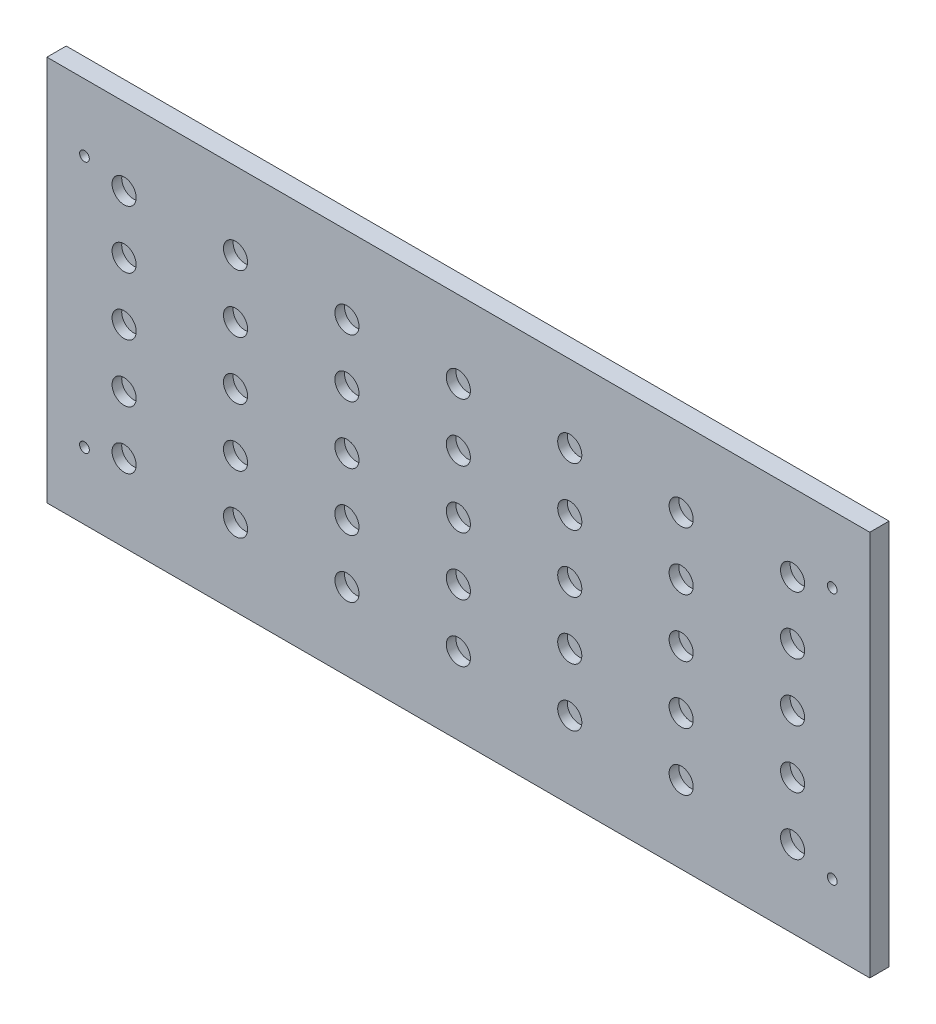
SolidWorks part; units mm, degrees
ref_plane "Front Plane" through (0, 0, 0) normal (0, 0, 1) x (1, 0, 0)
ref_plane "Top Plane" through (0, 0, 0) normal (0, 1, 0) x (1, 0, 0)
ref_plane "Right Plane" through (0, 0, 0) normal (1, 0, 0) x (0, 0, -1)
sketch "Sketch1" plane through (0, 0, 0) normal (0, 0, 1) x (1, 0, 0)
  line L0 (135.35, 127) -> (135.35, 0) construction
  line L1 (0, 0) -> (270.7, 0)
  line L2 (0, 0) -> (0, 127)
  line L3 (0, 127) -> (270.7, 127)
  line L4 (270.7, 0) -> (270.7, 127)
  line L5 (0, 63.5) -> (270.7, 63.5) construction
  circle A3 centre (12.35, 105) radius 1.6
  circle A7 centre (258.35, 105) radius 1.6
  circle A8 centre (258.35, 22) radius 1.6
  circle A9 centre (12.35, 22) radius 1.6
  dimension "D11" = 3.2
  dimension "D1" = 127
  dimension "D2" = 270.7
  dimension "D12" = 12.35
  dimension "D13" = 22
extrude "Wall" add sketch "Sketch1" along normal blind 6.35
sketch "Sketch2" plane through (0, 0, 6.35) normal (0, 0, 1) x (1, 0, 0)
  line L0 (135.35, 127) -> (135.35, 98.425) construction
  line L1 (270.7, 127) -> (0, 127) construction
  line L2 (135.35, 98.425) -> (66.6667, 98.425) construction
  line L3 (135.35, 98.425) -> (204.0333, 98.425) construction
  line L4 (0, 127) -> (0, 0) construction
  circle A0 centre (135.35, 98.425) radius 3.9687
  circle A1 centre (66.6667, 98.425) radius 3.9688
  circle A2 centre (204.0333, 98.425) radius 3.9687
  dimension "D2" = 7.9375
  dimension "D1" = 28.575
  dimension "D3" = 66.6667
extrude "RodSupportCutouts" [suppressed] cut sketch "Sketch2" against normal up to next
sketch "Sketch3" plane through (0, 0, 6.35) normal (0, 0, 1) x (1, 0, 0)
  line L1 (25.4, 88.9) -> (245.3, 88.9)
  line L2 (25.4, 88.9) -> (25.4, 114.3)
  line L3 (25.4, 114.3) -> (245.3, 114.3)
  line L4 (245.3, 88.9) -> (245.3, 114.3)
  line L5 (25.4, 88.9) -> (245.3, 114.3) construction
  line L6 (25.4, 114.3) -> (245.3, 88.9) construction
  line L7 (270.7, 127) -> (0, 127) construction
  line L8 (0, 127) -> (0, 0) construction
  point P0 (135.35, 101.6)
  point P9 (135.35, 127)
  dimension "D1" = 25.4
  dimension "D2" = 25.4
  dimension "D3" = 25.4
extrude "CannulaLargeCutout" [suppressed] cut sketch "Sketch3" against normal up to next
sketch "Sketch4" [suppressed] plane through (0, 0, 9.525) normal (0, 0, 1) x (1, 0, 0)
  line L0 (6, 103.5) -> (194, 103.5) construction
  line L1 (6, 105) -> (6, 22) construction
  line L2 (194, 105) -> (194, 22) construction
  line L3 (200, 127) -> (0, 127) construction
  line L4 (0, 127) -> (0, 0) construction
  circle A0 centre (60, 103.5) radius 6.35
  circle A1 centre (20, 103.5) radius 6.35
  circle A2 centre (100, 103.5) radius 6.35
  circle A3 centre (140, 103.5) radius 6.35
  circle A4 centre (60, 63.5) radius 6.35
  circle A5 centre (100, 63.5) radius 6.35
  circle A6 centre (140, 63.5) radius 6.35
  circle A7 centre (60, 23.5) radius 6.35
  circle A8 centre (100, 23.5) radius 6.35
  circle A9 centre (140, 23.5) radius 6.35
  circle A10 centre (20, 63.5) radius 6.35
  circle A11 centre (20, 23.5) radius 6.35
  circle A12 centre (180, 103.5) radius 6.35
  circle A13 centre (180, 63.5) radius 6.35
  circle A14 centre (180, 23.5) radius 6.35
  point P42 (100, 127)
  point P45 (0, 63.5)
  dimension "D3" = 12.7
  dimension "D1" = 5
  dimension "D2" = 3
extrude "CannulaHoles" [suppressed] cut sketch "Sketch4" against normal up to next
ref_plane "LeftBoundary" through (25.4, 0, 0) normal (-1, 0, 0) x (0, 0, 1)
ref_plane "RightBoundary" through (245.3, 0, 0) normal (1, 0, 0) x (0, 0, -1)
ref_plane "TopBoundary" through (0, 101.6, 0) normal (0, 1, 0) x (1, 0, 0)
ref_plane "BottomBoundary" through (0, 25.4, 0) normal (0, -1, 0) x (-1, 0, 0)
sketch "Sketch5" plane through (0, 0, 6.35) normal (0, 0, 1) x (1, 0, 0)
  line L4 (25.4, 3.4925) -> (25.4, -3.4925) construction
  line L5 (3.4925, 101.6) -> (-3.4925, 101.6) construction
  circle A0 centre (25.4, 101.6) radius 3.9687
  dimension "D1" = 7.9375
extrude "RodSupportCutout" cut sketch "Sketch5" against normal blind 3.175 from surface at 0 starting at face at (135.35, 63.5, 6.35)
pattern_linear "SupportPattern" count 7 spacing 36.65 along (1, 0, 0) count 5 spacing 19.05 along (0, -1, 0) of "RodSupportCutout"
equation "\"Length\"= 283mm"
equation "\"Width\"= 225mm"
equation "\"WallThickness\"= 0.25in"
equation "\"UpperWaterJacketThickness\"= 28mm"
equation "\"SpacerHeight\"= 80.2mm"
equation "\"SpacerCornerWidth\"= 10mm"
equation "\"SpacerCornerHeight\"= 60.16mm"
equation "\"SpacerPegDiameter\"= 10mm"
equation "\"SpacerPegHeight\"= 10mm"
equation "\"TubingShort\"= 110mm"
equation "\"TubingLong\"= 175mm"
equation "\"PlateLength\"= 252mm"
equation "\"PlateWidth\"= 190mm"
equation "\"PlateHoleDiameter\"= 5.9mm"
equation "\"PlateHoleBottom\"= 2mm"
equation "\"PlateHoleSide\"= 1.55mm"
equation "\"PlateHoleSpacing\"= 3.1mm"
equation "\"PlateThickness\"= 1.55mm"
equation "\"ReservoirBottom\"= 12.5mm"
equation "\"ReservoirSupportWidth\"= 12mm"
equation "\"ReservoirSupportHeight\"= 15.1mm"
equation "\"ReservoirSupportPlacementHeight\"= 50mm"
equation "\"ReservoirHoleDiameter\"= 12.7mm"
equation "\"ReservoirHoleRight\"= 25mm"
equation "\"ReservoirHoleTop\"= \"ReservoirSupportPlacementHeight\""
equation "\"ReservoirHeight\"= 90mm"
equation "\"ReservoirPortBottom\"= 4mm"
equation "\"ReservoirPortTop\"= 10mm"
equation "\"ReservoirPortWidth\"= 101mm"
equation "\"CustomSpacerHeight\"= 5in"
equation "\"CustomSpacerRodHoleHeight\"= .75in"
equation "\"CustomSpacerRodHoleDiameter\"= .3125in"
equation "\"ScrewBlockSide\"= 12mm"
equation "\"ScrewBlockUpperHeight\"= 16mm"
equation "\"ScrewBlockLowerHeight\"= 16mm"
equation "\"InternalLength\"= 258mm"
equation "\"InternalWidth\"= 200mm"
equation "\"CustomSpacerPegHeight\"= 1in"
equation "\"CustomSpacerScrewBore\"=3.2mm"
equation "\"CustomSpacerScrewDepth\"=10mm"
equation "\"D1@Sketch1\"=\"CustomSpacerHeight\""
equation "\"D2@Sketch1\"=\"WallLength\""
equation "\"D11@Sketch1\"=\"CustomSpacerScrewBore\""
equation "\"D12@Sketch1\"  = \"ScrewBlockSide\"/2 + \"WallThickness\""
equation "\"D13@Sketch1\"=\"ScrewBlockUpperHeight\"+\"ScrewBlockSide\"/2"
equation "\"D1@Wall\" = \"WallThickness\""
equation "\"D1@Sketch2\"=\"CustomSpacerRodHoleHeight\" + \"CustomSpacerRodHoleDiameter\" +0.0625in"
equation "\"D2@Sketch2\"=\"CustomSpacerRodHoleDiameter\""
equation "\"D3@Sketch2\"=\"InternalWidth\" / 3"
equation "\"D1@Sketch3\"=1in"
equation "\"WallLength\"= \"InternalLength\" + ( 2 * \"WallThickness\" )"
equation "\"D1@Sketch5\"=\"CustomSpacerRodHoleDiameter\""
equation "\"D1@RodSupportCutout\"=\"WallThickness\" / 2"
